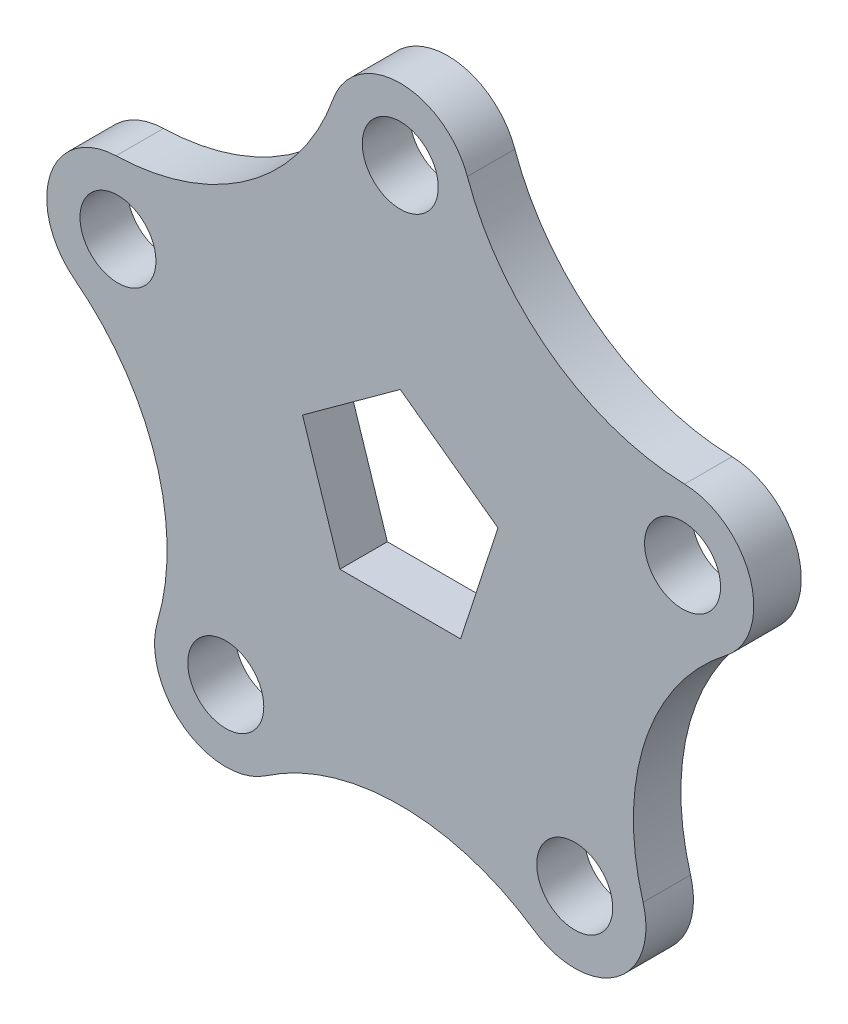
SolidWorks part; units mm, degrees
ref_plane "Front Plane" through (0, 0, 0) normal (0, 0, 1) x (1, 0, 0)
ref_plane "Top Plane" through (0, 0, 0) normal (0, 1, 0) x (1, 0, 0)
ref_plane "Right Plane" through (0, 0, 0) normal (1, 0, 0) x (0, 0, -1)
sketch "Sketch1" plane through (0, 0, 0) normal (0, 0, 1) x (1, 0, 0)
  line L0 (0, 62.5) -> (0, -21.8078) construction
  line L7 (20.5725, 6.6844) -> (0, 21.6312)
  line L8 (0, 21.6312) -> (-20.5725, 6.6844)
  line L9 (-20.5725, 6.6844) -> (-12.7145, -17.5)
  line L10 (-12.7145, -17.5) -> (12.7145, -17.5)
  line L11 (12.7145, -17.5) -> (20.5725, 6.6844)
  circle A0 centre (0, 0) radius 17.5 construction
  circle A12 centre (0, 0) radius 62.5 construction
  circle A13 centre (0, 62.5) radius 8
  arc A14 (14.1321, 67.5282) -> (-14.1321, 67.5282) centre (0, 62.5) ccw
  circle A15 centre (59.441, 19.3136) radius 8
  arc A16 (68.5902, 7.4269) -> (59.856, 34.3078) centre (59.441, 19.3136) ccw
  circle A17 centre (36.7366, -50.5636) radius 8
  arc A18 (28.2589, -62.9381) -> (51.1252, -46.3248) centre (36.7366, -50.5636) ccw
  circle A19 centre (-36.7366, -50.5636) radius 8
  arc A20 (-51.1252, -46.3248) -> (-28.2589, -62.9381) centre (-36.7366, -50.5636) ccw
  circle A21 centre (-59.441, 19.3136) radius 8
  arc A22 (-59.856, 34.3078) -> (-68.5902, 7.4269) centre (-59.441, 19.3136) ccw
  arc A23 (14.1321, 67.5282) -> (59.856, 34.3078) centre (61.2393, 84.2887) ccw
  arc A24 (68.5902, 7.4269) -> (51.1252, -46.3248) centre (99.0873, -32.1954) ccw
  arc A25 (28.2589, -62.9381) -> (-28.2589, -62.9381) centre (0, -104.1865) ccw
  arc A26 (-51.1252, -46.3248) -> (-68.5902, 7.4269) centre (-99.0873, -32.1954) ccw
  arc A27 (-59.856, 34.3078) -> (-14.1321, 67.5282) centre (-61.2393, 84.2887) ccw
  point P13 (0, 0)
  point P27 (0, 0)
  point P43 (0, 0)
  dimension "D1" = 35
  dimension "D2" = 125
  dimension "D3" = 16
  dimension "D4" = 30
  dimension "D5" = 50
  dimension "D6" = 5
  dimension "D7" = 5
extrude "Boss-Extrude1" add sketch "Sketch1" along normal blind 10
